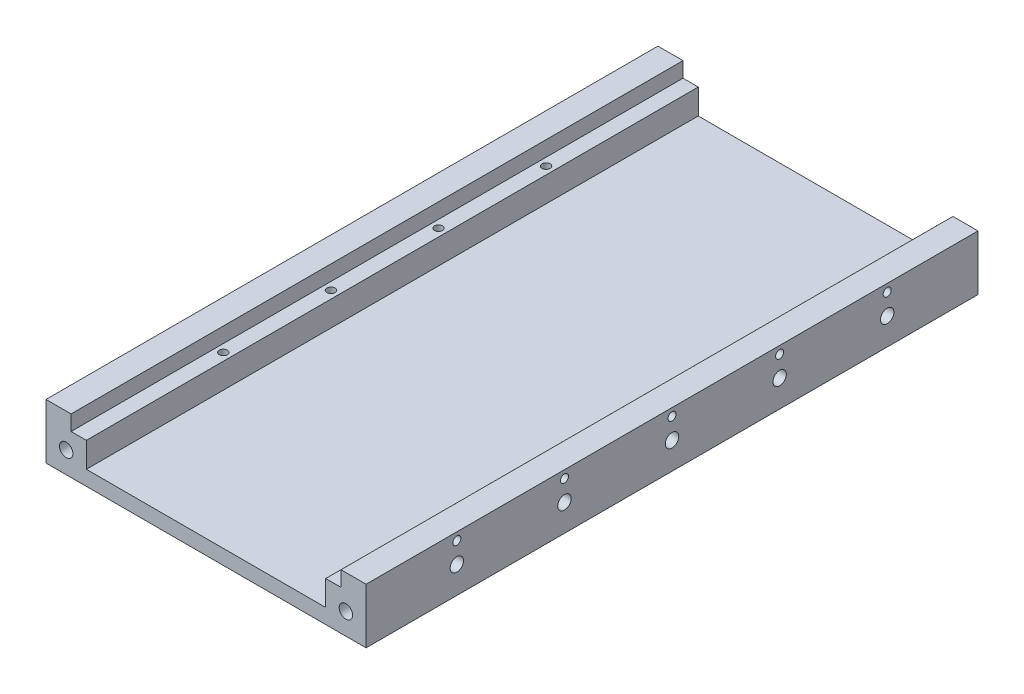
SolidWorks part; units mm, degrees
material "Aluminum"
ref_plane "Front Plane" through (0, 0, 0) normal (0, 0, 1) x (1, 0, 0)
ref_plane "Top Plane" through (0, 0, 0) normal (0, 1, 0) x (1, 0, 0)
ref_plane "Right Plane" through (0, 0, 0) normal (1, 0, 0) x (0, 0, -1)
sketch "Sketch1" plane through (0, 0, 0) normal (0, 0, 1) x (1, 0, 0)
  line L1 (44.5, 5.5) -> (-44.5, 5.5)
  line L6 (84.1457, 0) -> (-84.1457, 0) construction
  line L7 (-59.5, 0) -> (59.5, 0) construction
  line L9 (59.5, 0) -> (-59.5, 0)
  line L22 (50.17, 20.5) -> (59.5, 20.5)
  line L23 (50.17, 14.835) -> (50.17, 20.5)
  line L24 (44.5, 14.835) -> (50.17, 14.835)
  line L25 (44.5, 5.5) -> (44.5, 14.835)
  line L26 (-50.17, 20.5) -> (-59.5, 20.5)
  line L27 (-50.17, 14.835) -> (-50.17, 20.5)
  line L28 (-44.5, 14.835) -> (-50.17, 14.835)
  line L29 (-44.5, 5.5) -> (-44.5, 14.835)
  line L30 (-59.5, 20.5) -> (-59.5, 0)
  line L31 (59.5, 20.5) -> (59.5, 0)
  point P0 (0, 0)
  point P10 (0, 0)
  dimension "D1" = 119
  dimension "D2" = 89
  dimension "D3" = 100.34
  dimension "D4" = 9.33
  dimension "D5" = 20.5
extrude "Boss-Extrude1" add sketch "Sketch1" along normal blind 227.5
hole_wizard "Tap Drill for M5x0.8 Tap1" positions "Sketch4" profile "Sketch2" hole size "M5x0.8" standard "ANSI Metric"
sketch "Sketch4" plane through (0, 0, 227.5) normal (0, 0, 1) x (1, 0, 0)
  line L0 (0, 0) -> (0, 90.9259) construction
  line L3 (0, 0) -> (-119.5026, 0) construction
  point P4 (52, 8)
  point P6 (-52, 8)
  dimension "D1" = 8
  dimension "D2" = 8
  dimension "D4" = 52
  dimension "D5" = 52
sketch "Sketch2" plane through (52, 8, 227.5) normal (1, 0, 0) x (0, -1, 0)
  line L0 (0, 0) -> (0, 10)
  line L1 (0, 10) -> (2.5, 10)
  line L2 (2.5, 10) -> (2.5, 0)
  line L5 (2.5, 0) -> (0, 0)
  line L10 (0, 10) -> (-2.5, 10) construction
  line L11 (0, -6.35) -> (0, 107.95) construction
  dimension "Hole Dia." = 5
  dimension "Hole Depth" = 10
  dimension "Drill Angle" = 180
hole_wizard "Tap Drill for M5x0.8 Tap2" positions "Sketch6" profile "Sketch5" hole size "M5x0.8" standard "ANSI Metric"
sketch "Sketch6" plane through (0, 0, 0) normal (0, 0, -1) x (-1, 0, 0)
  point P0 (52, 8)
  point P3 (-52, 8)
sketch "Sketch5" plane through (-52, 8, 0) normal (1, 0, 0) x (0, 1, 0)
  line L0 (0, 0) -> (0, 10)
  line L1 (0, 10) -> (2.5, 10)
  line L2 (2.5, 10) -> (2.5, 0)
  line L5 (2.5, 0) -> (0, 0)
  line L10 (0, 10) -> (-2.5, 10) construction
  line L11 (0, -6.35) -> (0, 107.95) construction
  dimension "Hole Dia." = 5
  dimension "Hole Depth" = 10
  dimension "Drill Angle" = 180
hole_wizard "Tap Drill for M5x0.8 Tap3" positions "Sketch8" profile "Sketch7" hole size "M5x0.8" standard "ANSI Metric"
sketch "Sketch8" plane through (59.5, 0, 0) normal (1, 0, 0) x (0, 0, -1)
  line L2 (-113.75, 0) -> (-113.75, 73.5941) construction
  line L3 (-227.5, 0) -> (0, 0) construction
  point P0 (-193.75, 10)
  point P4 (-153.75, 10)
  point P6 (-113.75, 10)
  point P8 (-73.75, 10)
  point P10 (-33.75, 10)
  dimension "D1" = 40
  dimension "D2" = 40
  dimension "D3" = 40
  dimension "D4" = 40
  dimension "D5" = 10
  dimension "D6" = 10
  dimension "D7" = 10
sketch "Sketch7" plane through (59.5, 10, 193.75) normal (0, 1, 0) x (0, 0, -1)
  line L0 (0, 0) -> (0, 10)
  line L1 (0, 10) -> (2.5, 10)
  line L2 (2.5, 10) -> (2.5, 0)
  line L5 (2.5, 0) -> (0, 0)
  line L10 (0, 10) -> (-2.5, 10) construction
  line L11 (0, -6.35) -> (0, 107.95) construction
  dimension "Hole Dia." = 5
  dimension "Hole Depth" = 10
  dimension "Drill Angle" = 180
hole_wizard "Tap Drill for M5x0.8 Tap4" positions "Sketch10" profile "Sketch9" hole size "M5x0.8" standard "ANSI Metric"
sketch "Sketch10" plane through (-59.5, 0, 0) normal (-1, 0, 0) x (0, 0, 1)
  point P0 (193.75, 10)
  point P3 (153.75, 10)
  point P6 (113.75, 10)
  point P9 (73.75, 10)
  point P12 (33.75, 10)
sketch "Sketch9" plane through (-59.5, 10, 193.75) normal (0, 1, 0) x (0, 0, 1)
  line L0 (0, 0) -> (0, 10)
  line L1 (0, 10) -> (2.5, 10)
  line L2 (2.5, 10) -> (2.5, 0)
  line L5 (2.5, 0) -> (0, 0)
  line L10 (0, 10) -> (-2.5, 10) construction
  line L11 (0, -6.35) -> (0, 107.95) construction
  dimension "Hole Dia." = 5
  dimension "Hole Depth" = 10
  dimension "Drill Angle" = 180
sketch "Sketch11" plane through (0, 0, 0) normal (0, -1, 0) x (1, 0, 0)
  line L0 (-59.5, 227.5) -> (-59.5, 0) construction
  line L1 (-59.5, 227.5) -> (59.5, 227.5) construction
  line L2 (-59.5, 0) -> (59.5, 0) construction
  line L5 (0, 227.5) -> (0, 0) construction
  circle A0 centre (-47.33, 173.75) radius 1.5
  circle A1 centre (-47.33, 133.75) radius 1.5
  circle A2 centre (-47.33, 93.75) radius 1.5
  circle A3 centre (-47.33, 53.75) radius 1.5
  circle A4 centre (47.33, 53.75) radius 1.5
  circle A5 centre (47.33, 93.75) radius 1.5
  circle A6 centre (47.33, 133.75) radius 1.5
  circle A7 centre (47.33, 173.75) radius 1.5
  dimension "D1" = 3
  dimension "D4" = 3
  dimension "D5" = 3
  dimension "D6" = 3
  dimension "D2" = 12.17
  dimension "D3" = 53.75
  dimension "D7" = 53.75
  dimension "D8" = 40
  dimension "D9" = 40
extrude "Cut-Extrude1" cut sketch "Sketch11" against normal blind 29
sketch "Sketch13" plane through (50.17, 0, 0) normal (-1, 0, 0) x (0, 0, 1)
  line L1 (193.75, 10) -> (193.75, -14.7863) construction
  line L2 (227.5, 20.5) -> (0, 20.5) construction
  circle A0 centre (193.75, 17.6675) radius 1.5
  circle A1 centre (153.75, 17.6675) radius 1.5
  circle A2 centre (113.75, 17.6675) radius 1.5
  circle A3 centre (73.75, 17.6675) radius 1.5
  circle A4 centre (33.75, 17.6675) radius 1.5
  dimension "D1" = 3
  dimension "D2" = 2.8325
  dimension "D3" = 5
extrude "Cut-Extrude2" cut sketch "Sketch13" against normal blind 29
